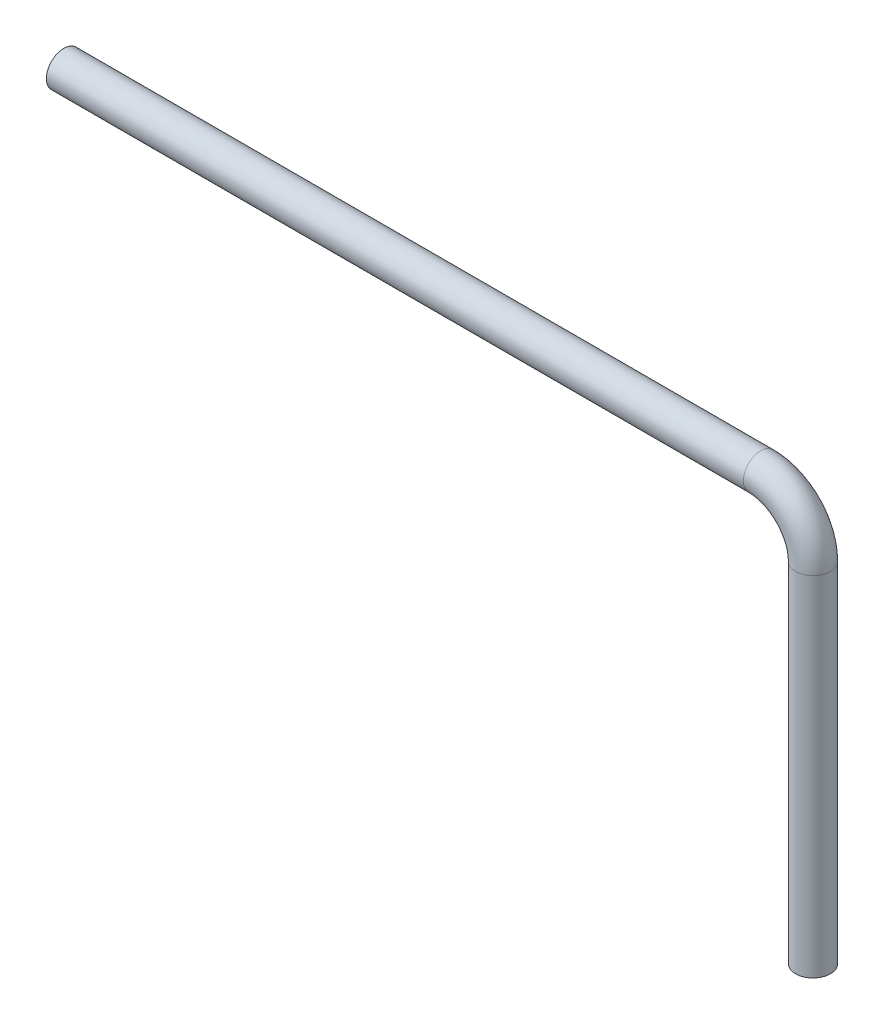
SolidWorks part; units mm, degrees
ref_plane "Front Plane" through (0, 0, 0) normal (0, 0, 1) x (1, 0, 0)
ref_plane "Top Plane" through (0, 0, 0) normal (0, 1, 0) x (1, 0, 0)
ref_plane "Right Plane" through (0, 0, 0) normal (1, 0, 0) x (0, 0, -1)
sketch "Sketch1" plane through (0, 0, 0) normal (0, 0, 1) x (1, 0, 0)
  line L0 (0, 0) -> (0, 500)
  line L1 (-75, 575) -> (-1075, 575)
  arc A0 (0, 500) -> (-75, 575) centre (-75, 500) ccw
  dimension "D2" = 75
  dimension "D3" = 90
  dimension "D1" = 500
  dimension "D4" = 1000
sketch "Sketch2" plane through (0, 0, 0) normal (0, 1, 0) x (1, 0, 0)
  circle A0 centre (0, 0) radius 25
  dimension "D1" = 50
sweep "Sweep1" add profiles "Sketch2" path "Sketch1"
